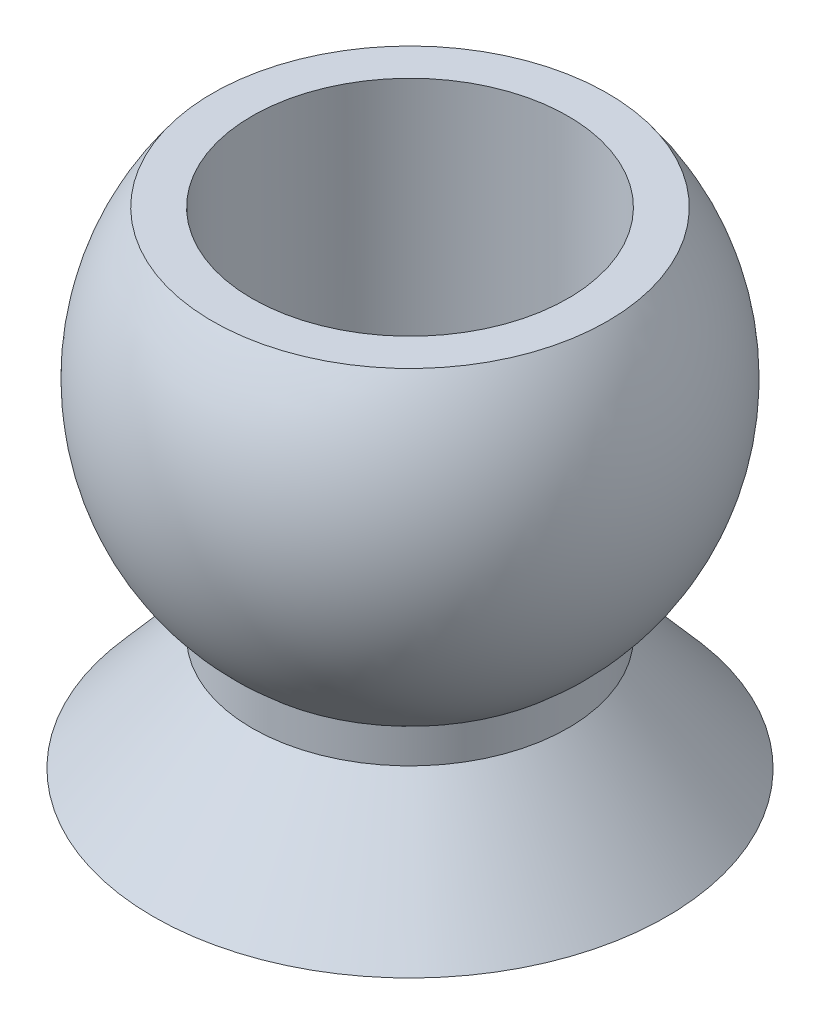
SolidWorks part; units mm, degrees
ref_plane "前视基准面" through (0, 0, 0) normal (0, 0, 1) x (1, 0, 0)
ref_plane "上视基准面" through (0, 0, 0) normal (0, 1, 0) x (1, 0, 0)
ref_plane "右视基准面" through (0, 0, 0) normal (1, 0, 0) x (0, 0, -1)
other "Configuration Table"
sketch "草图1" plane through (0, 0, 0) normal (0, 0, 1) x (1, 0, 0)
  line L0 (0, 1.25) -> (0, -1.25)
  arc A0 (0, -1.25) -> (0, 1.25) centre (0, 0) ccw
  dimension "D1" = 2.5
revolve "旋转1" add sketch "草图1" angle 360 about L0
ref_plane "基准面1" through (0, 0.75, 0) normal (0, 1, 0) x (1, 0, 0)
sketch "草图2" plane through (0, 0.75, 0) normal (0, 1, 0) x (1, 0, 0)
  circle A1 centre (0, 0) radius 1.0376
  dimension "D1" = 2.0753
extrude "切除-拉伸1" cut sketch "草图2" along normal blind 10
sketch "草图3" plane through (0, 0.75, 0) normal (0, 1, 0) x (1, 0, 0)
  circle A0 centre (0, 0) radius 0.8
  dimension "D1" = 1.6
extrude "切除-拉伸2" cut sketch "草图3" against normal blind 10
sketch "草图4" plane through (0, 0, 0) normal (1, 0, 0) x (0, 0, -1)
  line L0 (0, -0.9605) -> (0, -1.7105)
  line L1 (-0.8, -0.9605) -> (0.8, -0.9605) construction
  line L2 (0, -1.7105) -> (1.3, -1.7105)
  line L3 (1.3, -1.7105) -> (0.8, -1.134)
  line L4 (0.8, -1.134) -> (0.8, -0.9605)
  line L5 (0, -0.9605) -> (0.8, -0.9605)
  dimension "D1" = 0.75
  dimension "D2" = 1.3
  dimension "D3" = 0.5765
revolve "旋转3" add sketch "草图4" angle 360 about L0
